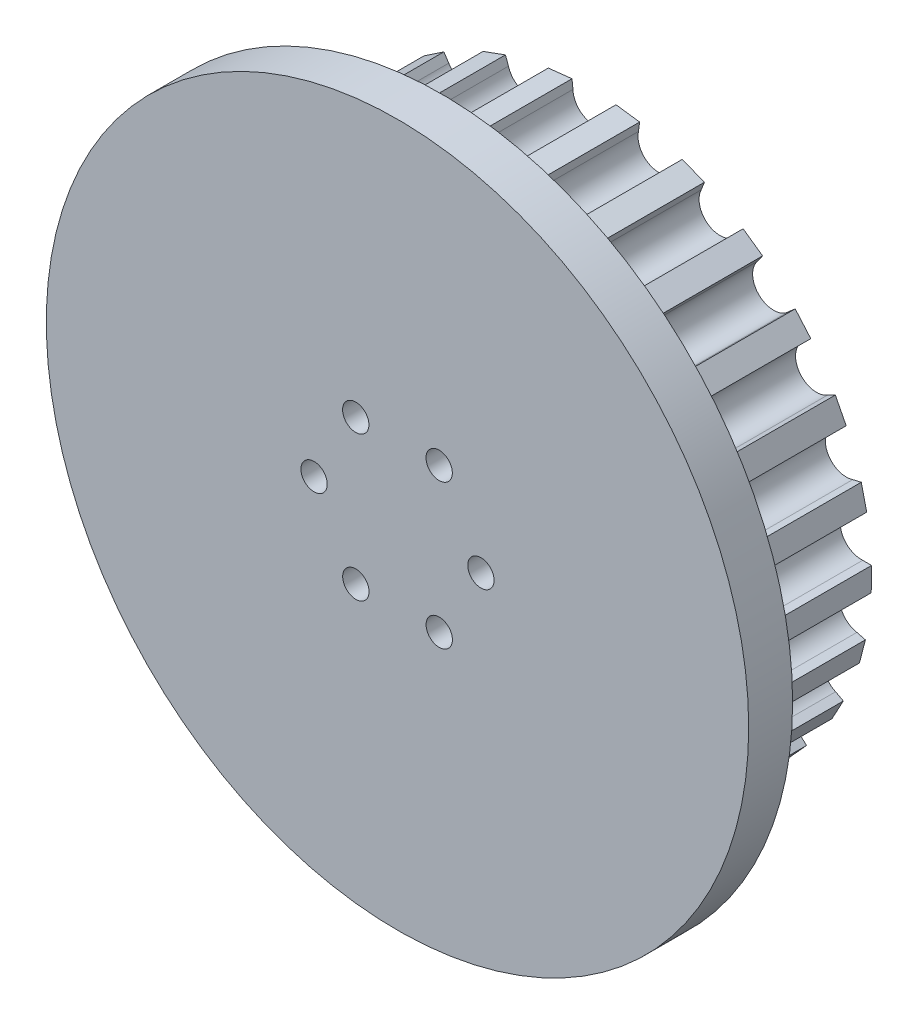
SolidWorks part; units mm, degrees
ref_plane "Front Plane" through (0, 0, 0) normal (0, 0, 1) x (1, 0, 0)
ref_plane "Top Plane" through (0, 0, 0) normal (0, 1, 0) x (1, 0, 0)
ref_plane "Right Plane" through (0, 0, 0) normal (1, 0, 0) x (0, 0, -1)
sketch "Sketch2" plane through (0, 0, 0) normal (0, 0, 1) x (1, 0, 0)
  line L0 (0.3691, 30.9978) -> (-7.0599, 30.1854) construction
  line L103 (-4.7156, 30.6392) -> (-4.8243, 31.6333)
  line L104 (-4.8243, 31.6333) -> (-2.1267, 31.9283)
  line L105 (-2.1267, 31.9283) -> (-2.018, 30.9342)
  line L106 (5.576, 31.5095) -> (5.4437, 30.5183)
  line L107 (2.7539, 30.8774) -> (2.8863, 31.8686)
  line L108 (2.8863, 31.8686) -> (5.576, 31.5095)
  line L109 (12.9547, 29.2595) -> (12.589, 28.3287)
  line L110 (10.0634, 29.3211) -> (10.4291, 30.2519)
  line L111 (10.4291, 30.2519) -> (12.9547, 29.2595)
  line L112 (19.5805, 25.309) -> (19.0027, 24.4928)
  line L113 (16.7879, 26.0608) -> (17.3658, 26.877)
  line L114 (17.3658, 26.877) -> (19.5805, 25.309)
  line L115 (25.0684, 19.8876) -> (24.312, 19.2334)
  line L116 (22.5369, 21.2859) -> (23.2932, 21.9401)
  line L117 (23.2932, 21.9401) -> (25.0684, 19.8876)
  line L118 (29.0994, 13.3104) -> (28.2084, 12.8563)
  line L119 (26.976, 15.2739) -> (27.867, 15.7281)
  line L120 (27.867, 15.7281) -> (29.0994, 13.3104)
  line L121 (31.4392, 5.9597) -> (30.4655, 5.732)
  line L122 (29.8475, 8.3743) -> (30.8212, 8.6021)
  line L123 (30.8212, 8.6021) -> (31.4392, 5.9597)
  line L124 (31.9519, -1.7373) -> (30.9519, -1.7254)
  line L125 (30.9843, 0.988) -> (31.9842, 0.9761)
  line L126 (31.9842, 0.9761) -> (31.9519, -1.7373)
  line L127 (30.6076, -9.3334) -> (29.6396, -9.0826)
  line L128 (30.3204, -6.4557) -> (31.2884, -6.7066)
  line L129 (31.2884, -6.7066) -> (30.6076, -9.3334)
  line L130 (27.4846, -16.3871) -> (26.6047, -15.9119)
  line L131 (27.8943, -13.5242) -> (28.7742, -13.9995)
  line L132 (28.7742, -13.9995) -> (27.4846, -16.3871)
  line L133 (22.7643, -22.4884) -> (22.0237, -21.8164)
  line L134 (23.8472, -19.8068) -> (24.5878, -20.4788)
  line L135 (24.5878, -20.4788) -> (22.7643, -22.4884)
  line L136 (16.7209, -27.2828) -> (16.1627, -26.4531)
  line L137 (18.4142, -24.9383) -> (18.9724, -25.768)
  line L138 (18.9724, -25.768) -> (16.7209, -27.2828)
  line L139 (9.7059, -30.4916) -> (9.3624, -29.5524)
  line L140 (11.911, -28.6204) -> (12.2544, -29.5596)
  line L141 (12.2544, -29.5596) -> (9.7059, -30.4916)
  line L142 (2.1267, -31.9283) -> (2.018, -30.9342)
  line L143 (4.7156, -30.6392) -> (4.8243, -31.6333)
  line L144 (4.8243, -31.6333) -> (2.1267, -31.9283)
  line L145 (-5.576, -31.5095) -> (-5.4437, -30.5183)
  line L146 (-2.7539, -30.8774) -> (-2.8863, -31.8686)
  line L147 (-2.8863, -31.8686) -> (-5.576, -31.5095)
  line L148 (-12.9547, -29.2595) -> (-12.589, -28.3287)
  line L149 (-10.0634, -29.3211) -> (-10.4291, -30.2519)
  line L150 (-10.4291, -30.2519) -> (-12.9547, -29.2595)
  line L151 (-19.5805, -25.309) -> (-19.0027, -24.4928)
  line L152 (-16.7879, -26.0608) -> (-17.3658, -26.877)
  line L153 (-17.3658, -26.877) -> (-19.5805, -25.309)
  line L154 (-25.0684, -19.8876) -> (-24.312, -19.2334)
  line L155 (-22.5369, -21.2859) -> (-23.2932, -21.9401)
  line L156 (-23.2932, -21.9401) -> (-25.0684, -19.8876)
  line L157 (-29.0994, -13.3104) -> (-28.2084, -12.8563)
  line L158 (-26.976, -15.2739) -> (-27.867, -15.7281)
  line L159 (-27.867, -15.7281) -> (-29.0994, -13.3104)
  line L160 (-31.4392, -5.9597) -> (-30.4655, -5.732)
  line L161 (-29.8475, -8.3743) -> (-30.8212, -8.6021)
  line L162 (-30.8212, -8.6021) -> (-31.4392, -5.9597)
  line L163 (-31.9519, 1.7373) -> (-30.9519, 1.7254)
  line L164 (-30.9843, -0.988) -> (-31.9842, -0.9761)
  line L165 (-31.9842, -0.9761) -> (-31.9519, 1.7373)
  line L166 (-30.6076, 9.3334) -> (-29.6396, 9.0826)
  line L167 (-30.3204, 6.4557) -> (-31.2884, 6.7066)
  line L168 (-31.2884, 6.7066) -> (-30.6076, 9.3334)
  line L169 (-27.4846, 16.3871) -> (-26.6047, 15.9119)
  line L170 (-27.8943, 13.5242) -> (-28.7742, 13.9995)
  line L171 (-28.7742, 13.9995) -> (-27.4846, 16.3871)
  line L172 (-22.7643, 22.4884) -> (-22.0237, 21.8164)
  line L173 (-23.8472, 19.8068) -> (-24.5878, 20.4788)
  line L174 (-24.5878, 20.4788) -> (-22.7643, 22.4884)
  line L175 (-16.7209, 27.2828) -> (-16.1627, 26.4531)
  line L176 (-18.4142, 24.9383) -> (-18.9724, 25.768)
  line L177 (-18.9724, 25.768) -> (-16.7209, 27.2828)
  line L178 (-9.7059, 30.4916) -> (-9.3624, 29.5524)
  line L179 (-11.911, 28.6204) -> (-12.2544, 29.5596)
  line L180 (-12.2544, 29.5596) -> (-9.7059, 30.4916)
  circle A0 centre (0, 0) radius 27.5
  circle A1 centre (0, 0) radius 31
  arc A103 (-4.7156, 30.6392) -> (-2.018, 30.9342) centre (0, 0) cw
  arc A104 (2.7539, 30.8774) -> (5.4437, 30.5183) centre (0, 0) cw
  arc A105 (10.0634, 29.3211) -> (12.589, 28.3287) centre (0, 0) cw
  arc A106 (16.7879, 26.0608) -> (19.0027, 24.4928) centre (0, 0) cw
  arc A107 (22.5369, 21.2859) -> (24.312, 19.2334) centre (0, 0) cw
  arc A108 (26.976, 15.2739) -> (28.2084, 12.8563) centre (0, 0) cw
  arc A109 (29.8475, 8.3743) -> (30.4655, 5.732) centre (0, 0) cw
  arc A110 (30.9843, 0.988) -> (30.9519, -1.7254) centre (0, 0) cw
  arc A111 (30.3204, -6.4557) -> (29.6396, -9.0826) centre (0, 0) cw
  arc A112 (27.8943, -13.5242) -> (26.6047, -15.9119) centre (0, 0) cw
  arc A113 (23.8472, -19.8068) -> (22.0237, -21.8164) centre (0, 0) cw
  arc A114 (18.4142, -24.9383) -> (16.1627, -26.4531) centre (0, 0) cw
  arc A115 (11.911, -28.6204) -> (9.3624, -29.5524) centre (0, 0) cw
  arc A116 (4.7156, -30.6392) -> (2.018, -30.9342) centre (0, 0) cw
  arc A117 (-2.7539, -30.8774) -> (-5.4437, -30.5183) centre (0, 0) cw
  arc A118 (-10.0634, -29.3211) -> (-12.589, -28.3287) centre (0, 0) cw
  arc A119 (-16.7879, -26.0608) -> (-19.0027, -24.4928) centre (0, 0) cw
  arc A120 (-22.5369, -21.2859) -> (-24.312, -19.2334) centre (0, 0) cw
  arc A121 (-26.976, -15.2739) -> (-28.2084, -12.8563) centre (0, 0) cw
  arc A122 (-29.8475, -8.3743) -> (-30.4655, -5.732) centre (0, 0) cw
  arc A123 (-30.9843, -0.988) -> (-30.9519, 1.7254) centre (0, 0) cw
  arc A124 (-30.3204, 6.4557) -> (-29.6396, 9.0826) centre (0, 0) cw
  arc A125 (-27.8943, 13.5242) -> (-26.6047, 15.9119) centre (0, 0) cw
  arc A126 (-23.8472, 19.8068) -> (-22.0237, 21.8164) centre (0, 0) cw
  arc A127 (-18.4142, 24.9383) -> (-16.1627, 26.4531) centre (0, 0) cw
  circle A128 centre (7.7766, 30.0087) radius 2.3879
  circle A129 centre (14.7322, 27.2757) radius 2.3879
  circle A130 centre (20.8316, 22.9575) radius 2.3879
  circle A131 centre (25.7203, 17.305) radius 2.3879
  circle A132 centre (29.1143, 10.6469) radius 2.3879
  circle A133 centre (30.8163, 3.37) radius 2.3879
  circle A134 centre (30.7273, -4.1027) radius 2.3879
  circle A135 centre (28.8526, -11.337) radius 2.3879
  circle A136 centre (25.301, -17.9125) radius 2.3879
  circle A137 centre (20.2791, -23.4469) radius 2.3879
  circle A138 centre (14.0786, -27.6187) radius 2.3879
  circle A139 centre (7.0599, -30.1854) radius 2.3879
  circle A140 centre (-0.3691, -30.9978) radius 2.3879
  circle A141 centre (-7.7766, -30.0087) radius 2.3879
  circle A142 centre (-14.7322, -27.2757) radius 2.3879
  circle A143 centre (-20.8316, -22.9575) radius 2.3879
  circle A144 centre (-25.7203, -17.305) radius 2.3879
  circle A145 centre (-29.1143, -10.6469) radius 2.3879
  circle A146 centre (-30.8163, -3.37) radius 2.3879
  circle A147 centre (-30.7273, 4.1027) radius 2.3879
  circle A148 centre (-28.8526, 11.337) radius 2.3879
  circle A149 centre (-25.301, 17.9125) radius 2.3879
  circle A150 centre (-20.2791, 23.4469) radius 2.3879
  circle A151 centre (-14.0786, 27.6187) radius 2.3879
  circle A152 centre (-7.0599, 30.1854) radius 2.3879
  circle A153 centre (0.3691, 30.9978) radius 2.3879
  arc A154 (-11.911, 28.6204) -> (-9.3624, 29.5524) centre (0, 0) cw
  point P64 (0, 0)
  point P79 (0, 0)
  point P164 (0, 0)
  point P176 (0, 0)
  point P178 (0, 0)
  point P185 (0, 0)
  point P269 (0, 0)
  point P363 (0, 0)
  dimension "D1" = 55
  dimension "D2" = 62
  dimension "D4" = 1
  dimension "D5" = 1
  dimension "D3" = 26
extrude "Boss-Extrude4" add sketch "Sketch2" against normal blind 17
sketch "Sketch6" plane through (0, 0, 0) normal (0, 0, 1) x (1, 0, 0)
  circle A0 centre (0, 0) radius 40
  dimension "D1" = 80
extrude "Boss-Extrude5" add sketch "Sketch6" along normal blind 5
sketch "Sketch9" plane through (0, 0, -17) normal (0, 0, -1) x (-1, 0, 0)
  circle A0 centre (0, 0) radius 22.5
  dimension "D1" = 45
extrude "Cut-Extrude2" cut sketch "Sketch9" against normal blind 8.9145
sketch "Sketch10" plane through (0, 0, -8.0855) normal (0, 0, -1) x (-1, 0, 0)
  circle A0 centre (0, 0) radius 9.5 construction
  circle A1 centre (-4.7446, 8.2304) radius 1.5
  circle A2 centre (4.7554, 8.2241) radius 1.5
  circle A3 centre (9.5, -0.0063) radius 1.5
  circle A4 centre (4.7446, -8.2304) radius 1.5
  circle A5 centre (-4.7554, -8.2241) radius 1.5
  circle A6 centre (-9.5, 0.0063) radius 1.5
  point P18 (0, 0)
  dimension "D1" = 19
  dimension "D2" = 3
  dimension "D3" = 6
extrude "Cut-Extrude3" cut sketch "Sketch10" against normal through all contours A1 | A6 | A5 | A4 | A3 | A2
